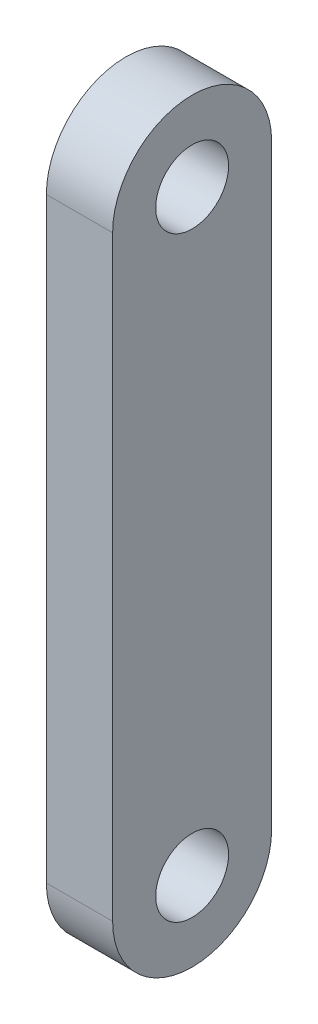
SolidWorks part; units mm, degrees
ref_plane "Front Plane" through (0, 0, 0) normal (1, 0, 0) x (0, 1, 0)
ref_plane "Top Plane" through (0, 0, 0) normal (0, 0, 1) x (0, 1, 0)
ref_plane "Right Plane" through (0, 0, 0) normal (0, 1, 0) x (-1, 0, 0)
sketch "Sketch1" plane through (0, 0, 0) normal (1, 0, 0) x (0, 1, 0)
  line L0 (0, 6) -> (45, 6)
  line L1 (0, -6) -> (45, -6)
  circle A0 centre (0, 0) radius 2.75
  arc A1 (0, 6) -> (0, -6) centre (0, 0) ccw
  arc A2 (45, -6) -> (45, 6) centre (45, 0) ccw
  circle A3 centre (45, 0) radius 2.75
  dimension "D2" = 12
  dimension "D3" = 12
  dimension "D4" = 5.5
  dimension "D5" = 5.5
  dimension "D1" = 45
extrude "Boss-Extrude1" add sketch "Sketch1" along normal blind 5
